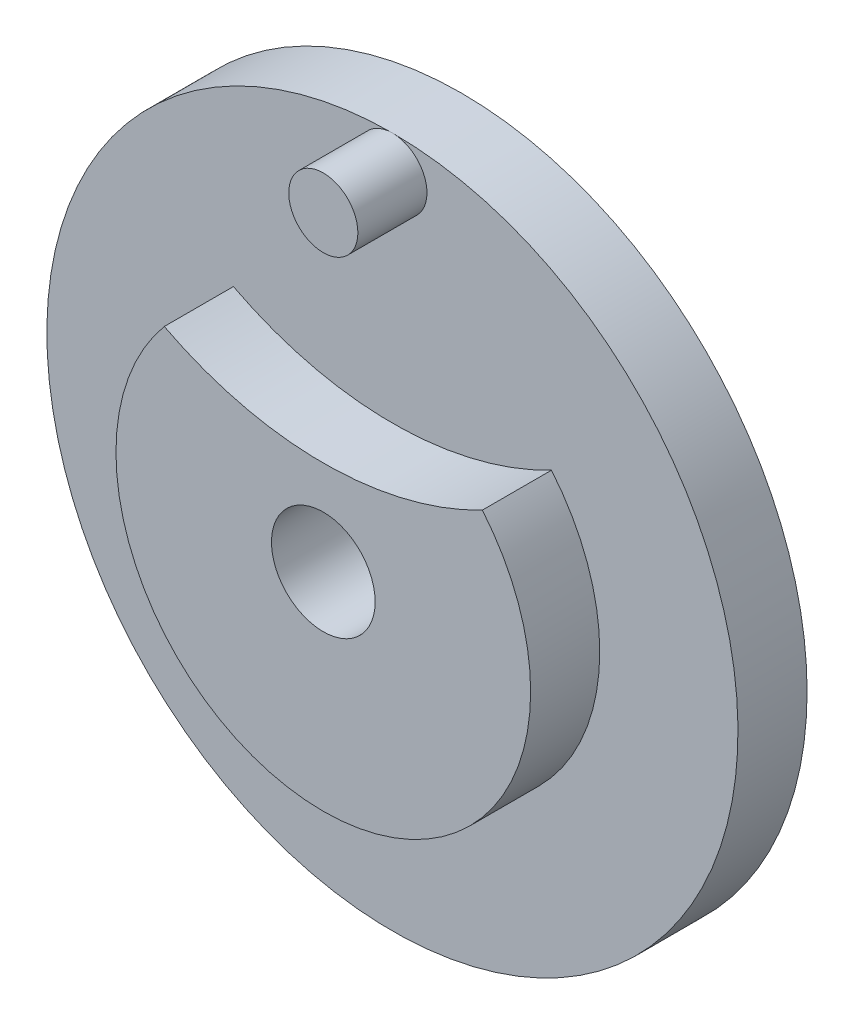
SolidWorks part; units mm, degrees
ref_plane "Front" through (0, 0, 0) normal (0, 0, 1) x (1, 0, 0)
ref_plane "Top" through (0, 0, 0) normal (0, 1, 0) x (1, 0, 0)
ref_plane "Right" through (0, 0, 0) normal (1, 0, 0) x (0, 0, -1)
sketch "Sketch1" plane through (0, 0, 0) normal (0, 0, 1) x (1, 0, 0)
  circle A0 centre (0, 0) radius 25
  dimension "D1" = 50
extrude "Boss-Extrude1" add sketch "Sketch1" along normal mid plane 5
sketch "Sketch3" plane through (0, 0, 0) normal (0, 0, 1) x (1, 0, 0)
  circle A0 centre (0, 22.5) radius 2.5
  circle A1 centre (0, 0) radius 25 construction
  arc A2 (-11.5052, 9.6245) -> (11.5052, 9.6245) centre (0, 0) ccw
  arc A3 (-11.5052, 9.6245) -> (11.5052, 9.6245) centre (0, 31.8198) ccw
  point P9 (0, 0)
  point P10 (0, 0)
  point P11 (0, 0)
  dimension "D1" = 5
  dimension "D2" = 30
  dimension "D3" = 50
  dimension "D4" = 31.8198
extrude "Boss-Extrude3" add sketch "Sketch3" along normal blind 7.5
sketch "Sketch5" plane through (0, 0, 7.5) normal (0, 0, 1) x (1, 0, 0)
  circle A0 centre (0, 0) radius 3.75
  dimension "D1" = 7.5
extrude "Cut-Extrude1" cut sketch "Sketch5" against normal through all
equation "\"12w\"=11.2691"
